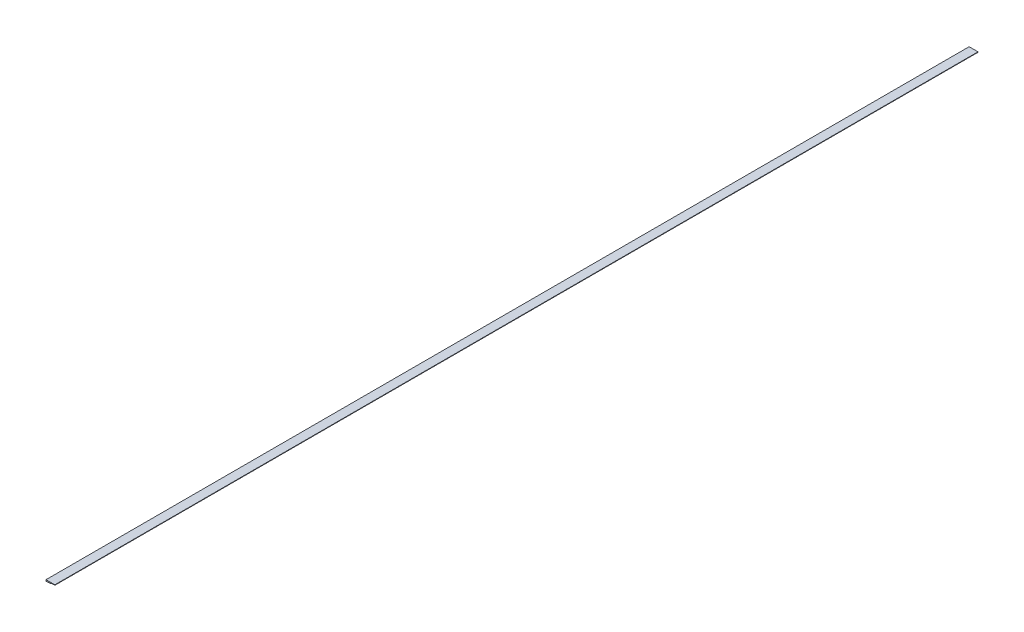
SolidWorks part; units mm, degrees
material "ASTM A500 Grade B Steel"
ref_plane "Front Plane" through (0, 0, 0) normal (0, 0, 1) x (1, 0, 0)
ref_plane "Top Plane" through (0, 0, 0) normal (0, 1, 0) x (1, 0, 0)
ref_plane "Right Plane" through (0, 0, 0) normal (1, 0, 0) x (0, 0, -1)
sketch "Sketch2" plane through (0, 0, 0) normal (0, 0, 1) x (1, 0, 0)
  line L0 (-7.6194, 25.4) -> (-32.6194, 23.2128)
  line L1 (-2103.2445, -157.9434) -> (-7.6194, 25.4) construction
  line L2 (-7.6194, 25.4) -> (-4.4444, 25.4)
  line L3 (-4.4444, 25.4) -> (-4.4444, 28.575)
  line L4 (-4.4444, 28.575) -> (17.3806, 28.575)
  line L5 (-4.4444, 28.575) -> (112.1612, 28.575) construction
  line L6 (17.3806, 28.575) -> (17.3806, 31.0863)
  line L7 (17.3806, 31.0863) -> (-32.6194, 31.0863)
  line L8 (-32.6194, 31.0863) -> (-32.6194, 23.2128)
  dimension "D1" = 25
  dimension "D2" = 25
extrude "Boss-Extrude1" add sketch "Sketch2" against normal up to surface (5214.4 mm away)
